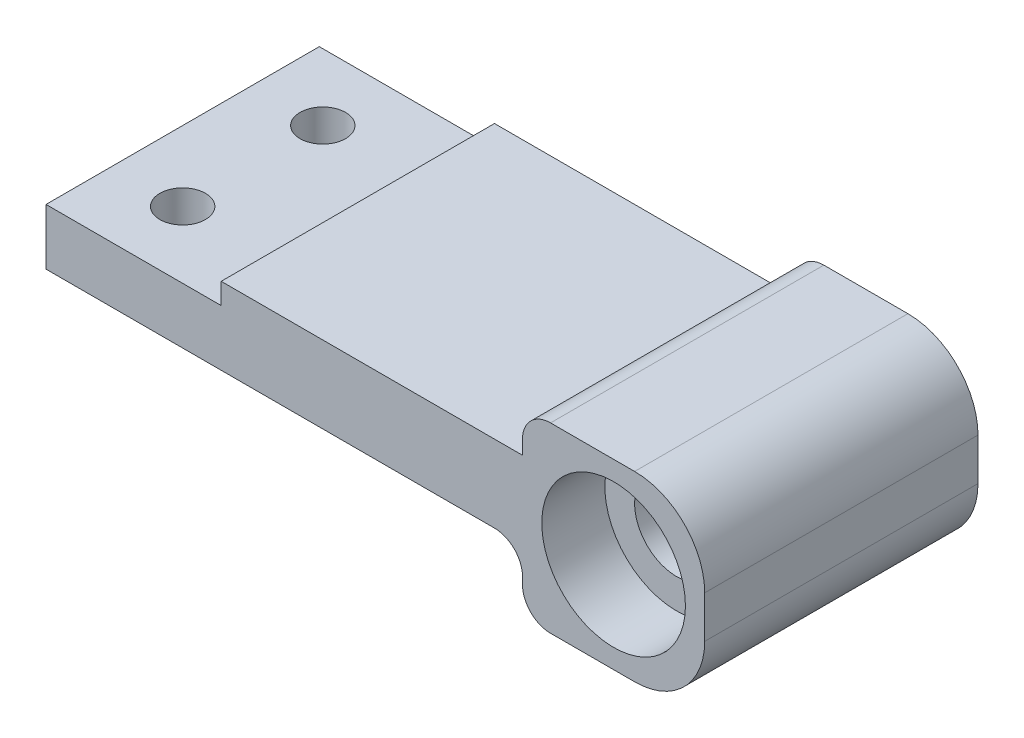
SolidWorks part; units mm, degrees
ref_plane "Ebene vorne" through (0, 0, 0) normal (0, 0, 1) x (1, 0, 0)
ref_plane "Ebene oben" through (0, 0, 0) normal (0, 1, 0) x (1, 0, 0)
ref_plane "Ebene rechts" through (0, 0, 0) normal (1, 0, 0) x (0, 0, -1)
sketch "Sketch1" plane through (0, 0, 0) normal (0, 0, 1) x (1, 0, 0)
  line L1 (6.5, -6.5) -> (-6.5, -6.5)
  line L2 (6.5, -6.5) -> (6.5, 6.5)
  line L3 (6.5, 6.5) -> (-6.5, 6.5)
  line L4 (-6.5, -6.5) -> (-6.5, 6.5)
  line L5 (6.5, -6.5) -> (-6.5, 6.5) construction
  line L6 (6.5, 6.5) -> (-6.5, -6.5) construction
  point P0 (0, 0)
  dimension "D1" = 13
  dimension "D2" = 13
extrude "Ball Bearing Block" add sketch "Sketch1" along normal blind 19.5
sketch "Sketch2" plane through (0, 0, 0) normal (0, 0, -1) x (1, 0, 0)
  line L0 (-40.5, 0) -> (-30.5906, 0) construction
  line L1 (-6.5, -2) -> (-40.5, -2)
  line L2 (-6.5, -2) -> (-6.5, 2)
  line L3 (-6.5, 2) -> (-40.5, 2)
  line L4 (-40.5, -2) -> (-40.5, 2)
  line L5 (-6.5, 0) -> (-18.074, 0) construction
  line L6 (-6.5, -6.5) -> (-6.5, 6.5) construction
  dimension "D1" = 4
  dimension "D2" = 34
extrude "Paddle Plate" add sketch "Sketch2" against normal up to surface (19.5 mm away) up to face at (0, 0, 19.5)
sketch "Sketch3" plane through (0, 0, 19.5) normal (0, 0, 1) x (1, 0, 0)
  circle A0 centre (0, 0) radius 5.125
  dimension "D1" = 10.25
extrude "Ballbearing 1" cut sketch "Sketch3" against normal blind 4.5
sketch "Sketch4" plane through (0, 0, 0) normal (0, 0, -1) x (1, 0, 0)
  circle A0 centre (0, 0) radius 5.125
  circle A1 centre (0, 0) radius 5.125 construction
extrude "Ballbearing 2" cut sketch "Sketch4" against normal blind 5
sketch "Sketch5" plane through (0, 0, 15) normal (0, 0, 1) x (1, 0, 0)
  circle A0 centre (0, 0) radius 3
  dimension "D1" = 6
extrude "Achse" cut sketch "Sketch5" against normal up to surface (10 mm away) up to face at (0, 5.125, 5)
sketch "Sketch9" plane through (0, 0, 5) normal (0, 0, -1) x (-1, 0, 0)
  circle A0 centre (0, 0) radius 3
extrude "Achse Closer" add sketch "Sketch9" against normal blind 0.25
fillet "Fillet1" radius 5 1 edges at (6.5, 6.5, 9.75)
fillet "Fillet2" radius 5 1 edges at (6.5, -6.5, 9.75)
fillet "Fillet3" radius 2 3 edges at (-6.5, 6.5, 9.75)
fillet "Fillet4" radius 2 1 edges at (-6.5, -6.5, 9.75)
fillet "Fillet7" radius 2 5 edges
sketch "Sketch6" plane through (0, 2, 0) normal (0, 1, 0) x (-1, 0, 0)
  line L0 (40.5, 9.75) -> (23.4297, 9.75) construction
  line L1 (40.5, 19.5) -> (40.5, 0) construction
  circle A0 centre (35.5, 4.75) radius 1.625
  circle A1 centre (35.5, 14.75) radius 1.625
  dimension "D1" = 3.25
  dimension "D2" = 5
  dimension "D3" = 5
extrude "M3 Paddle Screws" cut sketch "Sketch6" against normal up to surface (4 mm away) up to face at (-16.5, -2, 9.75)
sketch "Sketch8" plane through (0, 2, 0) normal (0, 1, 0) x (-1, 0, 0)
  line L0 (40.5, 0) -> (6.5, 0) construction
  line L1 (28, 0) -> (6.5, 0)
  line L2 (28, 0) -> (28, 19.5)
  line L3 (28, 19.5) -> (6.5, 19.5)
  line L4 (6.5, 0) -> (6.5, 19.5)
  line L5 (40.5, 19.5) -> (6.5, 19.5) construction
  line L6 (40.5, 19.5) -> (40.5, 0) construction
  line L7 (6.5, 19.5) -> (6.5, 0) construction
  dimension "D2" = 12.5
extrude "Top Plate" add sketch "Sketch8" along normal blind 1.5
sketch "Sketch7" plane through (0, -2, 0) normal (0, 1, 0) x (-1, 0, 0)
  line L0 (40.5, 9.75) -> (26.7911, 9.75) construction
  line L1 (40.5, 19.5) -> (40.5, 0) construction
  circle A0 centre (19, 9.75) radius 7.75
  dimension "D1" = 15.5
  dimension "D2" = 16
extrude "Magnet Pocket" cut sketch "Sketch7" along normal offset from surface (3.75 mm away) 1.75 up to face at (-17.25, 3.5, 9.75)
